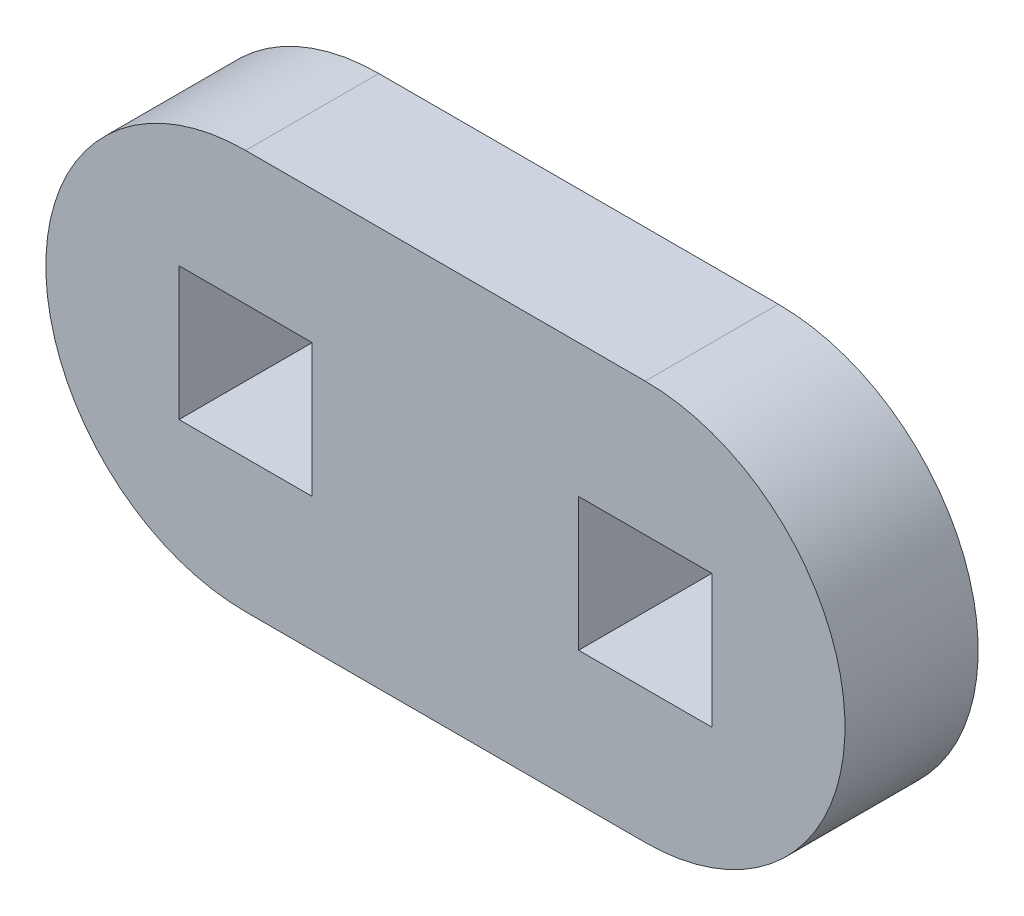
SolidWorks part; units mm, degrees
ref_plane "Alzado" through (0, 0, 0) normal (0, 0, 1) x (1, 0, 0)
ref_plane "Planta" through (0, 0, 0) normal (0, 1, 0) x (1, 0, 0)
ref_plane "Vista lateral" through (0, 0, 0) normal (1, 0, 0) x (0, 0, -1)
sketch "Model" plane through (0, 0, 0) normal (0, 0, 1) x (1, 0, 0)
  line L0 (11.1038, 295.7834) -> (11.1038, 292.7834)
  line L1 (14.1038, 295.7834) -> (11.1038, 295.7834)
  line L2 (14.1038, 292.7834) -> (14.1038, 295.7834)
  line L3 (11.1038, 292.7834) -> (14.1038, 292.7834)
  line L4 (20.1038, 295.7834) -> (20.1038, 292.7834)
  line L5 (23.1038, 295.7834) -> (20.1038, 295.7834)
  line L6 (23.1038, 292.7834) -> (23.1038, 295.7834)
  line L7 (20.1038, 292.7834) -> (23.1038, 292.7834)
  line L8 (12.6038, 298.7834) -> (21.6038, 298.7834)
  line L9 (12.6038, 289.7834) -> (21.6038, 289.7834)
  arc A0 (12.6038, 298.7834) -> (12.6038, 289.7834) centre (12.6038, 294.2834) ccw
  arc A1 (21.6038, 289.7834) -> (21.6038, 298.7834) centre (21.6038, 294.2834) ccw
extrude "Saliente-Extruir1" add sketch "Model" along normal blind 3
